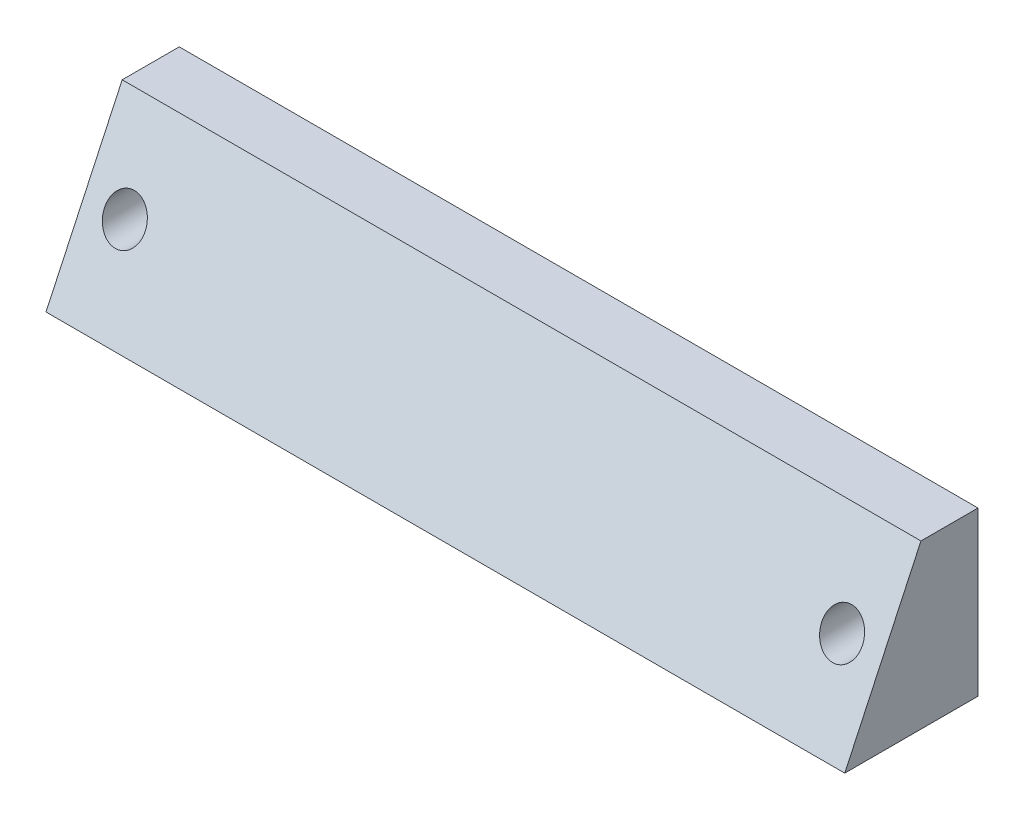
SolidWorks part; units mm, degrees
ref_plane "前视基准面" through (0, 0, 0) normal (0, 0, 1) x (1, 0, 0)
ref_plane "上视基准面" through (0, 0, 0) normal (0, 1, 0) x (1, 0, 0)
ref_plane "右视基准面" through (0, 0, 0) normal (1, 0, 0) x (0, 0, -1)
sketch "草图1" plane through (0, 0, 0) normal (0, 0, 1) x (1, 0, 0)
  line L1 (-48.2304, 25.3979) -> (49.7696, 25.3979)
  line L2 (-48.2304, 25.3979) -> (-48.2304, 5.3979)
  line L3 (-48.2304, 5.3979) -> (49.7696, 5.3979)
  line L4 (49.7696, 25.3979) -> (49.7696, 5.3979)
  dimension "D1" = 98
  dimension "D2" = 20
extrude "凸台-拉伸1" add sketch "草图1" along normal blind 7
sketch "草图2" plane through (-48.2304, 0, 0) normal (-1, 0, 0) x (0, 0, 1)
  line L0 (7, 25.3979) -> (7, 5.3979)
  line L1 (7, 5.3979) -> (12.8643, 5.3979)
  line L2 (12.8643, 5.3979) -> (16.3479, 5.3979)
  line L3 (16.3479, 5.3979) -> (7, 25.3979)
extrude "凸台-拉伸2" add sketch "草图2" against normal blind 98
sketch "草图3" plane through (0, 0, 0) normal (0, 0, -1) x (-1, 0, 0)
  line L0 (-0.7696, 25.3979) -> (-0.7696, 5.3979) construction
  line L1 (-49.7696, 25.3979) -> (48.2304, 25.3979) construction
  line L2 (48.2304, 5.3979) -> (-49.7696, 5.3979) construction
  line L3 (-49.7696, 15.3979) -> (48.2304, 15.3979) construction
  line L4 (-49.7696, 5.3979) -> (-49.7696, 25.3979) construction
  line L5 (48.2304, 25.3979) -> (48.2304, 5.3979) construction
  circle A0 centre (-44.7696, 15.3979) radius 1.5 construction
  circle A1 centre (43.2304, 15.3979) radius 1.5
  circle A2 centre (-44.7696, 15.3979) radius 2.5
  circle A3 centre (43.2304, 15.3979) radius 2.5
  dimension "D2" = 3
  dimension "D1" = 44
  dimension "D3" = 1
  dimension "D4" = 1
extrude "切除-拉伸3" cut sketch "草图3" against normal blind 98 from offset 6 offset against normal yes
sketch "草图4" plane through (0, 0, 0) normal (0, 0, 1) x (1, 0, 0)
  line L0 (0.7696, 25.3979) -> (0.7696, 5.3979) construction
  line L3 (-48.2304, 15.3979) -> (49.7696, 15.3979) construction
  line L6 (-48.2304, 5.3979) -> (-48.2304, 25.3979) construction
  circle A0 centre (-43.2304, 15.3979) radius 1.5
  circle A1 centre (44.7696, 15.3979) radius 1.5
  dimension "D2" = 3
  dimension "D1" = 44
  dimension "D3" = 49
extrude "切除-拉伸6" cut sketch "草图4" along normal blind 98
